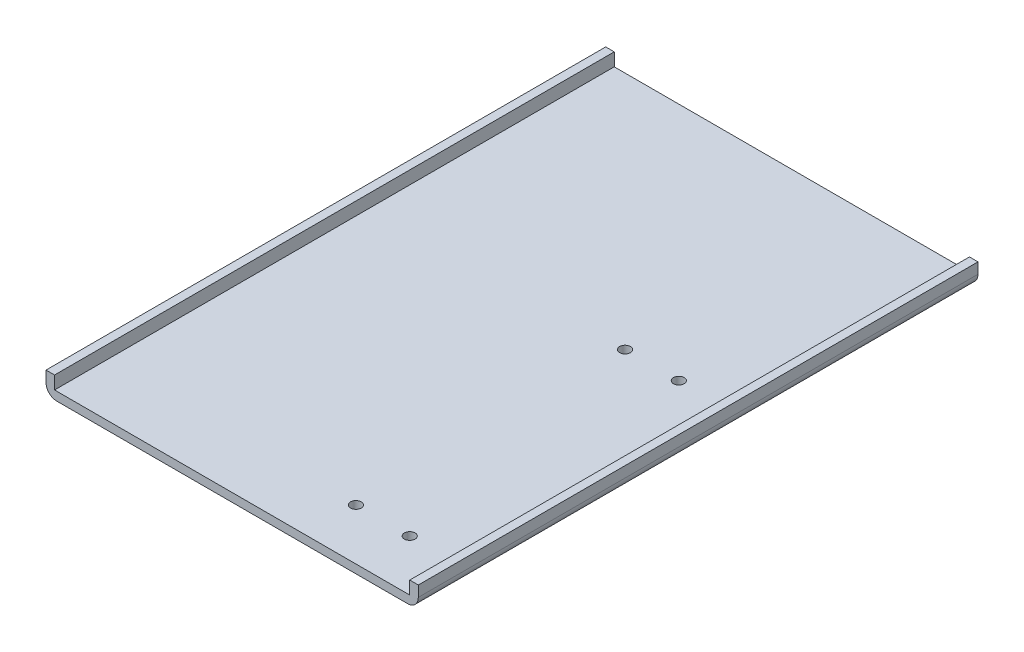
SolidWorks part; units mm, degrees
ref_plane "Plan de face" through (0, 0, 0) normal (0, 0, 1) x (1, 0, 0)
ref_plane "Plan de dessus" through (0, 0, 0) normal (0, 1, 0) x (1, 0, 0)
ref_plane "Plan de droite" through (0, 0, 0) normal (1, 0, 0) x (0, 0, -1)
sketch "Esquisse1" plane through (0, 0, 0) normal (0, 1, 0) x (1, 0, 0)
  line L1 (-33, -52) -> (33, -52)
  line L2 (-33, -52) -> (-33, 52)
  line L3 (-33, 52) -> (33, 52)
  line L4 (33, -52) -> (33, 52)
  line L5 (-33, -52) -> (33, 52) construction
  line L6 (-33, 52) -> (33, -52) construction
  point P0 (0, 0)
  dimension "D1" = 104
  dimension "D2" = 66
extrude "Boss.-Extru.1" add sketch "Esquisse1" along normal blind 1.5875
sketch "Esquisse2" plane through (-33, 0, 0) normal (-1, 0, 0) x (0, 0, 1)
  line L1 (-52, 0) -> (52, 0)
  line L2 (-52, 0) -> (-52, 4)
  line L3 (-52, 4) -> (52, 4)
  line L4 (52, 0) -> (52, 4)
  dimension "D1" = 4
  dimension "D2" = 104
extrude "Boss.-Extru.2" add sketch "Esquisse2" along normal blind 1.5875 contours L3 L4 L1 L2
sketch "Esquisse3" plane through (33, 0, 0) normal (1, 0, 0) x (0, 0, -1)
  line L1 (-52, 0) -> (52, 0)
  line L2 (-52, 0) -> (-52, 4)
  line L3 (-52, 4) -> (52, 4)
  line L4 (52, 0) -> (52, 4)
  dimension "D1" = 104
  dimension "D2" = 4
extrude "Boss.-Extru.3" add sketch "Esquisse3" along normal blind 1.5875
fillet "Congé2" radius 2 1 edges at (34.5875, 0, 0)
fillet "Congé3" radius 2 1 edges at (-34.5875, 0, 0)
sketch "Esquisse4" plane through (0, 1.5875, 0) normal (0, 1, 0) x (1, 0, 0)
  line L0 (23.5, -26.6977) -> (33, -26.6977) construction
  line L1 (23.5, -42.5) -> (13.5, -42.5) construction
  line L2 (23.5, -42.5) -> (23.5, 7.5) construction
  line L3 (23.5, 7.5) -> (13.5, 7.5) construction
  line L4 (13.5, -42.5) -> (13.5, 7.5) construction
  line L5 (33, -52) -> (33, 52) construction
  line L6 (19.3226, -42.5) -> (19.3226, -52) construction
  line L7 (-33, -52) -> (33, -52) construction
  circle A0 centre (13.5, 7.5) radius 1
  circle A1 centre (23.5, 7.5) radius 1
  circle A2 centre (23.5, -42.5) radius 1
  circle A3 centre (13.5, -42.5) radius 1
  dimension "D5" = 2
  dimension "D1" = 50
  dimension "D2" = 10
  dimension "D3" = 9.5
  dimension "D4" = 9.5
extrude "Enlèv. mat.-Extru.1" cut sketch "Esquisse4" against normal blind 1.5875 contours A0 | A1 | A3 | A2
